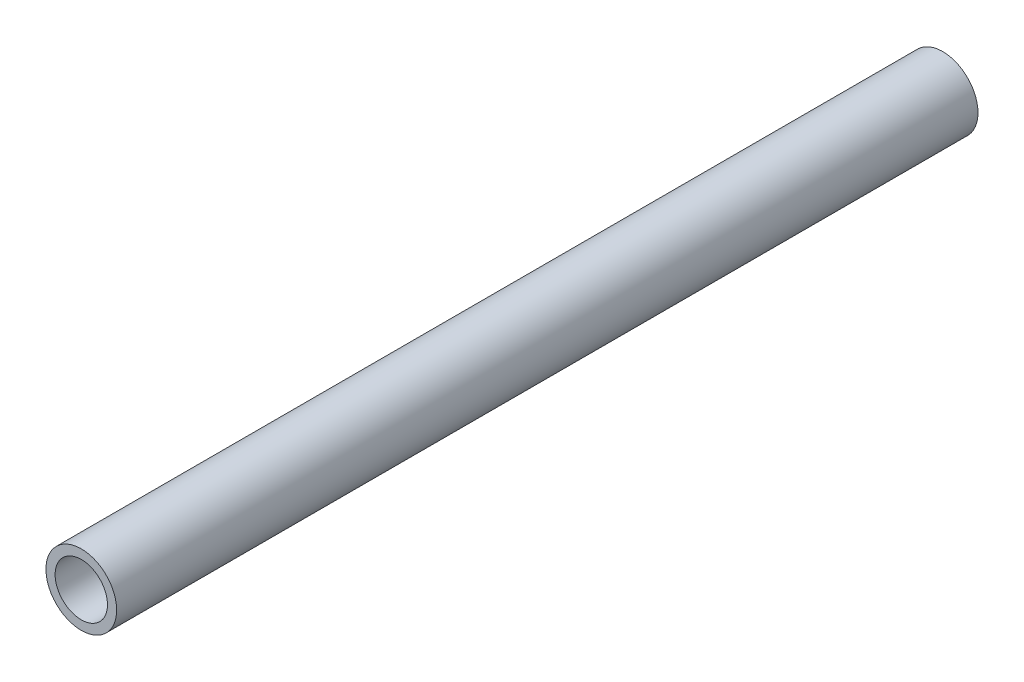
SolidWorks part; units mm, degrees
ref_plane "Front Plane" through (0, 0, 0) normal (0, 0, 1) x (1, 0, 0)
ref_plane "Top Plane" through (0, 0, 0) normal (0, 1, 0) x (1, 0, 0)
ref_plane "Right Plane" through (0, 0, 0) normal (1, 0, 0) x (0, 0, -1)
sketch "Sketch1" plane through (0, 0, 0) normal (0, 0, 1) x (1, 0, 0)
  circle A0 centre (0, 0) radius 10.668
  dimension "Pipe OD" = 21.336
extrude "Extrude-Thin1" add sketch "Sketch1" along normal mid plane 260 thin thin type one direction reverse wall 2.7686
